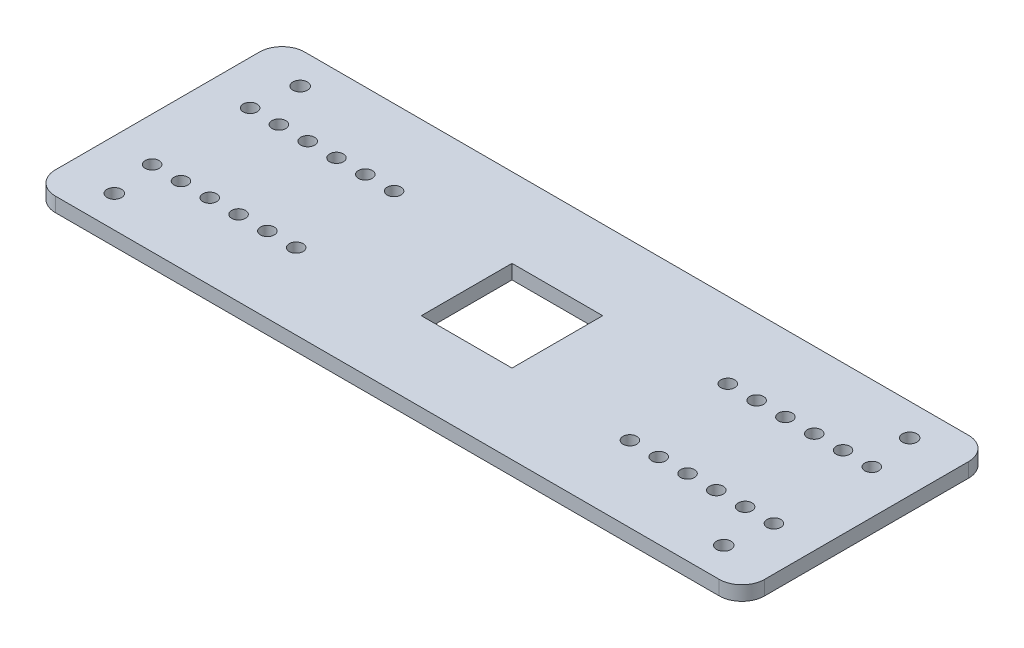
SolidWorks part; units mm, degrees
ref_plane "Front Plane" through (0, 0, 0) normal (0, 0, 1) x (1, 0, 0)
ref_plane "Top Plane" through (0, 0, 0) normal (0, 1, 0) x (1, 0, 0)
ref_plane "Right Plane" through (0, 0, 0) normal (1, 0, 0) x (0, 0, -1)
sketch "Sketch1" plane through (0, 0, 0) normal (0, 1, 0) x (1, 0, 0)
  line L1 (-78.2, 27.5) -> (78.2, 27.5)
  line L2 (-78.2, 27.5) -> (-78.2, -27.5)
  line L3 (-78.2, -27.5) -> (78.2, -27.5)
  line L4 (78.2, 27.5) -> (78.2, -27.5)
  line L5 (-78.2, 27.5) -> (78.2, -27.5) construction
  line L6 (-78.2, -27.5) -> (78.2, 27.5) construction
  point P0 (0, 0)
  dimension "D1" = 156.4
  dimension "D2" = 55
extrude "Boss-Extrude1" add sketch "Sketch1" along normal blind 3.175
sketch "Sketch2" plane through (0, 3.175, 0) normal (0, 1, 0) x (1, 0, 0)
  line L0 (0, 0) -> (-78.2, 0) construction
  line L1 (-78.2, 27.5) -> (-78.2, -27.5) construction
  line L2 (-78.2, 0) -> (78.2, 0) construction
  line L3 (78.2, -27.5) -> (78.2, 27.5) construction
  line L4 (78.2, 0) -> (0, 0) construction
  line L5 (0, 0) -> (0, 27.5) construction
  line L6 (78.2, 27.5) -> (-78.2, 27.5) construction
  line L7 (0, 27.5) -> (0, -27.5) construction
  line L8 (-78.2, -27.5) -> (78.2, -27.5) construction
  arc A0 (-67.024, -10.795) -> (-70.072, -10.795) centre (-68.548, -10.795) ccw construction
  arc A1 (-60.674, -10.795) -> (-63.722, -10.795) centre (-62.198, -10.795) ccw construction
  arc A2 (-54.324, -10.795) -> (-57.372, -10.795) centre (-55.848, -10.795) ccw construction
  arc A3 (-47.974, -10.795) -> (-51.022, -10.795) centre (-49.498, -10.795) ccw construction
  arc A4 (-41.624, -10.795) -> (-44.672, -10.795) centre (-43.148, -10.795) ccw construction
  arc A5 (-35.274, -10.795) -> (-38.322, -10.795) centre (-36.798, -10.795) ccw construction
  arc A6 (-67.024, -10.795) -> (-70.072, -10.795) centre (-68.548, -10.795) ccw construction
  arc A7 (-60.674, -10.795) -> (-63.722, -10.795) centre (-62.198, -10.795) ccw construction
  arc A8 (-54.324, -10.795) -> (-57.372, -10.795) centre (-55.848, -10.795) ccw construction
  arc A9 (-47.974, -10.795) -> (-51.022, -10.795) centre (-49.498, -10.795) ccw construction
  arc A10 (-41.624, -10.795) -> (-44.672, -10.795) centre (-43.148, -10.795) ccw construction
  arc A11 (-35.274, -10.795) -> (-38.322, -10.795) centre (-36.798, -10.795) ccw construction
  circle A12 centre (-68.548, -10.795) radius 1.524
  circle A13 centre (-62.198, -10.795) radius 1.524
  circle A14 centre (-55.848, -10.795) radius 1.524
  circle A15 centre (-49.498, -10.795) radius 1.524
  circle A16 centre (-43.148, -10.795) radius 1.524
  circle A17 centre (-36.798, -10.795) radius 1.524
  circle A18 centre (-68.548, 10.795) radius 1.524
  circle A19 centre (-62.198, 10.795) radius 1.524
  circle A20 centre (-55.848, 10.795) radius 1.524
  circle A21 centre (-49.498, 10.795) radius 1.524
  circle A22 centre (-43.148, 10.795) radius 1.524
  circle A23 centre (-36.798, 10.795) radius 1.524
  circle A24 centre (36.798, 10.795) radius 1.524
  circle A25 centre (43.148, 10.795) radius 1.524
  circle A26 centre (49.498, 10.795) radius 1.524
  circle A27 centre (55.848, 10.795) radius 1.524
  circle A28 centre (62.198, 10.795) radius 1.524
  circle A29 centre (68.548, 10.795) radius 1.524
  circle A30 centre (68.548, -10.795) radius 1.524
  circle A31 centre (62.198, -10.795) radius 1.524
  circle A32 centre (55.848, -10.795) radius 1.524
  circle A33 centre (49.498, -10.795) radius 1.524
  circle A34 centre (43.148, -10.795) radius 1.524
  circle A35 centre (36.798, -10.795) radius 1.524
extrude "Cut-Extrude1" cut sketch "Sketch2" against normal through all
sketch "Sketch4" plane through (0, 3.175, 0) normal (0, 1, 0) x (1, 0, 0)
  line L0 (-78.2, 0) -> (78.2, 0) construction
  line L1 (-78.2, -27.5) -> (-67.2, -27.5) construction
  line L2 (-78.2, -27.5) -> (-78.2, -20.5) construction
  line L3 (-78.2, -20.5) -> (-67.2, -20.5) construction
  line L4 (-67.2, -27.5) -> (-67.2, -20.5) construction
  line L5 (-78.2, -27.5) -> (-67.2, -20.5) construction
  line L6 (-78.2, -20.5) -> (-67.2, -27.5) construction
  line L7 (-78.2, 27.5) -> (-78.2, -27.5) construction
  line L8 (78.2, -27.5) -> (78.2, 27.5) construction
  line L9 (78.2, 0) -> (0, 0) construction
  line L10 (0, 0) -> (0, 27.5) construction
  line L11 (78.2, 27.5) -> (-78.2, 27.5) construction
  line L12 (0, 27.5) -> (0, -27.5) construction
  line L13 (-78.2, -27.5) -> (78.2, -27.5) construction
  circle A0 centre (-67.2, -20.5) radius 1.6
  circle A1 centre (-67.2, 20.5) radius 1.6
  circle A2 centre (67.2, 20.5) radius 1.6
  circle A3 centre (67.2, -20.5) radius 1.6
  point P4 (-72.7, -24)
  dimension "D3" = 3.2
  dimension "D1" = 11
  dimension "D2" = 7
extrude "Cut-Extrude2" cut sketch "Sketch4" against normal through all
sketch "Sketch5" plane through (0, 3.175, 0) normal (0, 1, 0) x (1, 0, 0)
  line L1 (-10, 10) -> (10, 10)
  line L2 (-10, 10) -> (-10, -10)
  line L3 (-10, -10) -> (10, -10)
  line L4 (10, 10) -> (10, -10)
  line L5 (-10, 10) -> (10, -10) construction
  line L6 (-10, -10) -> (10, 10) construction
  point P0 (0, 0)
  dimension "D1" = 20
  dimension "D2" = 20
extrude "Cut-Extrude3" cut sketch "Sketch5" against normal through all
fillet "Fillet1" radius 5 4 edges at (-78.2, 1.5875, 27.5) (78.2, 1.5875, 27.5) (-78.2, 1.5875, -27.5) (78.2, 1.5875, -27.5)
